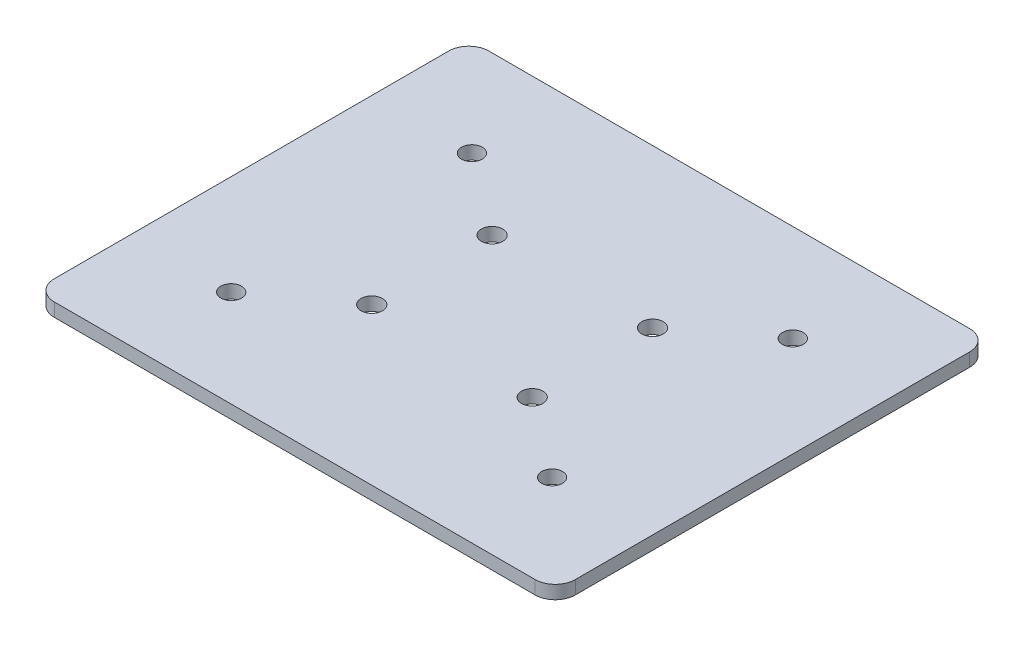
SolidWorks part; units mm, degrees
ref_plane "Front Plane" through (0, 0, 0) normal (0, 0, 1) x (1, 0, 0)
ref_plane "Top Plane" through (0, 0, 0) normal (0, 1, 0) x (1, 0, 0)
ref_plane "Right Plane" through (0, 0, 0) normal (1, 0, 0) x (0, 0, -1)
sketch "Sketch1" plane through (0, 0, 0) normal (0, 1, 0) x (1, 0, 0)
  line L1 (-38.9641, -32.5) -> (38.9641, -32.5)
  line L2 (-38.9641, -32.5) -> (-38.9641, 32.5)
  line L3 (-38.9641, 32.5) -> (38.9641, 32.5)
  line L4 (38.9641, -32.5) -> (38.9641, 32.5)
  line L5 (-38.9641, -32.5) -> (38.9641, 32.5) construction
  line L6 (-38.9641, 32.5) -> (38.9641, -32.5) construction
  line L7 (-24, 18) -> (24, 18)
  line L8 (-24, 18) -> (-24, -18)
  line L9 (-24, -18) -> (24, -18)
  line L10 (24, 18) -> (24, -18)
  line L11 (-24, 18) -> (24, -18) construction
  line L12 (-24, -18) -> (24, 18) construction
  circle A0 centre (-24, 18) radius 1.55
  circle A1 centre (24, 18) radius 1.55
  circle A2 centre (-24, -18) radius 1.55
  circle A3 centre (24, -18) radius 1.55
  point P0 (0, 0)
  point P6 (0, 0)
extrude "Boss-Extrude1" add sketch "Sketch1" along normal blind 2 contours L3 L4 L1 L2
sketch "Sketch2" plane through (0, 2, 0) normal (0, 1, 0) x (1, 0, 0)
  line L0 (-38.9641, 32.5) -> (38.9641, -32.5) construction
  circle A0 centre (-24, 18) radius 1.55
  circle A1 centre (24, 18) radius 1.55
  circle A2 centre (24, -18) radius 1.55
  circle A3 centre (-24, -18) radius 1.55
  circle A4 centre (-11.865, 8.8874) radius 1.6
  circle A5 centre (12.135, 8.8874) radius 1.6
  circle A6 centre (12.135, -9.1126) radius 1.6
  circle A7 centre (-11.865, -9.1126) radius 1.6
  point P12 (0.135, -0.1126)
extrude "Cut-Extrude3" cut sketch "Sketch2" against normal through all both and the other way through all
fillet "Fillet1" radius 3 4 edges at (-38.9641, 1, 32.5) (38.9641, 1, 32.5) (38.9641, 1, -32.5) (-38.9641, 1, -32.5)
